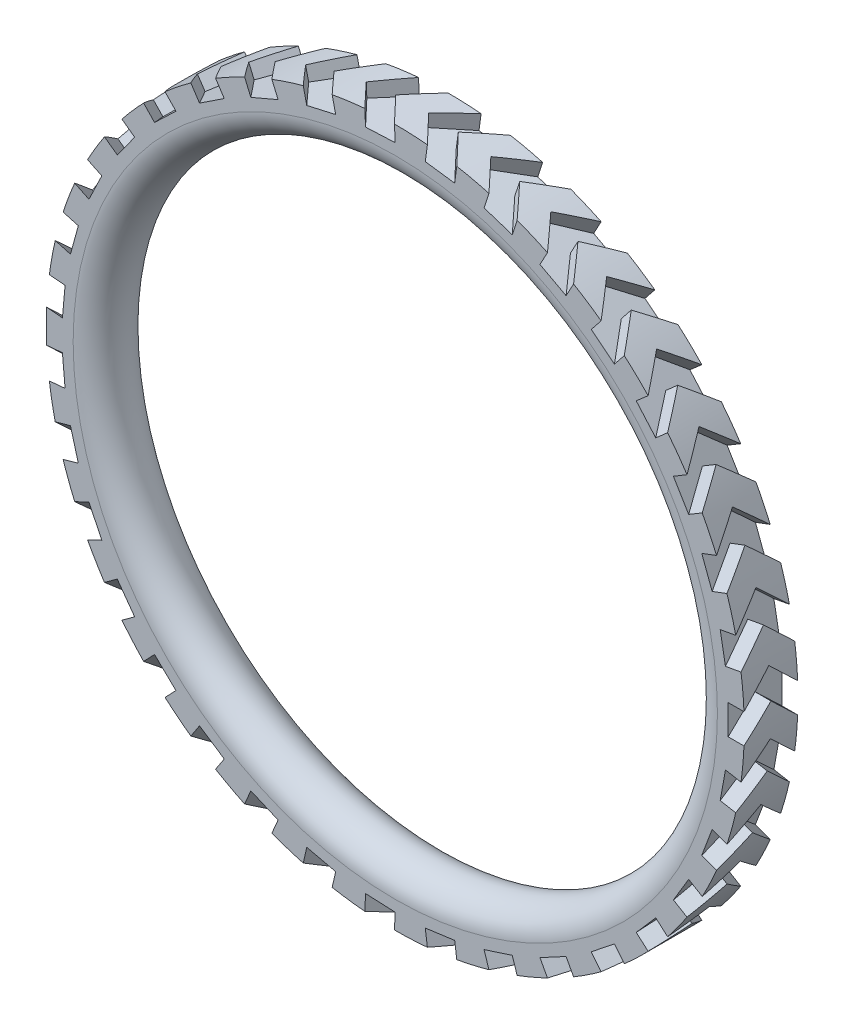
SolidWorks part; units mm, degrees
ref_plane "Plano frontal" through (0, 0, 0) normal (0, 0, 1) x (1, 0, 0)
ref_plane "Plano superior" through (0, 0, 0) normal (0, 1, 0) x (1, 0, 0)
ref_plane "Plano direito" through (0, 0, 0) normal (1, 0, 0) x (0, 0, -1)
sketch "Esboço1" plane through (0, 0, 0) normal (0, 0, 1) x (1, 0, 0)
  circle A0 centre (0, 0) radius 30
  dimension "D1" = 60
sketch "Esboço2" plane through (0, 0, 0) normal (1, 0, 0) x (0, 0, -1)
  line L1 (0, 30) -> (0, -30) construction
  line L2 (0, 32.5) -> (2.5, 32.5)
  line L3 (2.5, 32.5) -> (2.5, 30)
  line L5 (-2.5, 30) -> (-2.5, 32.5)
  line L6 (-2.5, 32.5) -> (0, 32.5)
  arc A0 (-2.5, 30) -> (2.5, 30) centre (0, 30) ccw
sweep "Varredura1" add profiles "Esboço2" path "Esboço1"
sketch "Esboço4" plane through (0, 0, 0) normal (1, 0, 0) x (0, 0, -1)
  line L1 (-2.5, 32.5) -> (-2.5, -32.5) construction
  line L3 (2.5, -32.5) -> (2.5, 32.5) construction
  line L5 (-2.5, -1.381) -> (0, 1)
  line L6 (0, 1) -> (2.5, -1.381)
  line L7 (2.5, -1.381) -> (0, 1)
  line L13 (-2.5, 1.381) -> (0, 3.7619)
  line L14 (0, 3.7619) -> (2.5, 1.381)
  line L15 (2.5, 1.381) -> (2.5, 0)
  line L16 (-2.5, 1.381) -> (-3.95, 0)
  line L17 (-3.95, 0) -> (-2.5, -1.381)
  line L18 (2.5, 1.381) -> (3.881, 0)
  line L19 (3.881, 0) -> (2.5, -1.381)
  line L20 (2.5, -1.381) -> (2.522, -1.4166)
extrude "Extrusão1" cut sketch "Esboço4" along normal blind 10 from offset 31 contours L16 L13 L14 L18 L19 L6 L5 L17
pattern_circular "Padrão circular2" count 35 over 360 about axis through (0, 0, 0) along (0, 0, 1) of "Extrusão1"
